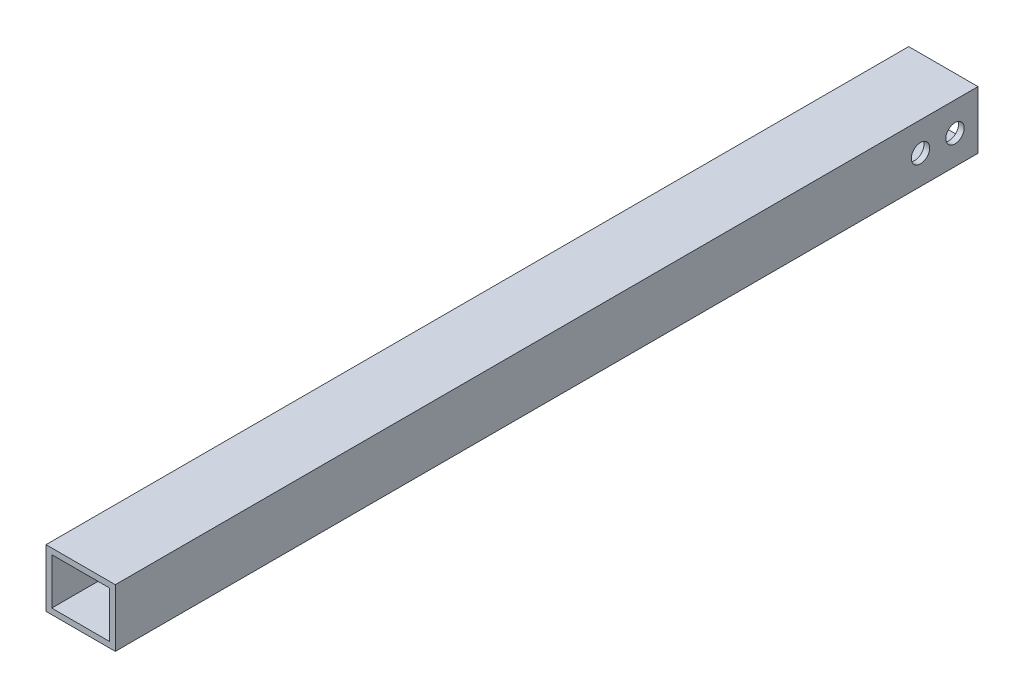
SolidWorks part; units mm, degrees
ref_plane "Plan de face" through (0, 0, 0) normal (0, 0, 1) x (1, 0, 0)
ref_plane "Plan de dessus" through (0, 0, 0) normal (0, 1, 0) x (1, 0, 0)
ref_plane "Plan de droite" through (0, 0, 0) normal (1, 0, 0) x (0, 0, -1)
sketch "Esquisse1" plane through (0, 0, 0) normal (0, 0, 1) x (1, 0, 0)
  line L1 (0, 0) -> (12.05, 0)
  line L2 (0, 0) -> (0, 10.05)
  line L3 (0, 10.05) -> (12.05, 10.05)
  line L4 (12.05, 0) -> (12.05, 10.05)
  dimension "D1" = 12.05
  dimension "D2" = 10.05
extrude "Extru.-Mince1" add sketch "Esquisse1" along normal blind 150 thin thin type one direction reverse wall 1
sketch "Esquisse2" plane through (0, 0, 0) normal (0, -1, 0) x (-1, 0, 0)
  line L0 (-6.025, -150) -> (-6.025, -80) construction
  line L1 (0, -150) -> (-12.05, -150) construction
  line L2 (-6.025, -80) -> (-12.05, -80) construction
  line L3 (-12.05, -150) -> (-12.05, 0) construction
  circle A0 centre (-6.025, -80) radius 1.6
  dimension "D1" = 3.2
  dimension "D2" = 70
extrude "Enlèv. mat.-Extru.1" cut sketch "Esquisse2" against normal up to next
sketch "Esquisse3" plane through (12.05, 0, 0) normal (1, 0, 0) x (0, 0, -1)
  circle A0 centre (-4, 5.025) radius 1.6
  circle A1 centre (-10, 5.025) radius 1.6
  dimension "D1" = 3.2
  dimension "D2" = 4
  dimension "D3" = 10
  dimension "D4" = 5.025
extrude "Enlèv. mat.-Extru.2" cut sketch "Esquisse3" against normal up to next
